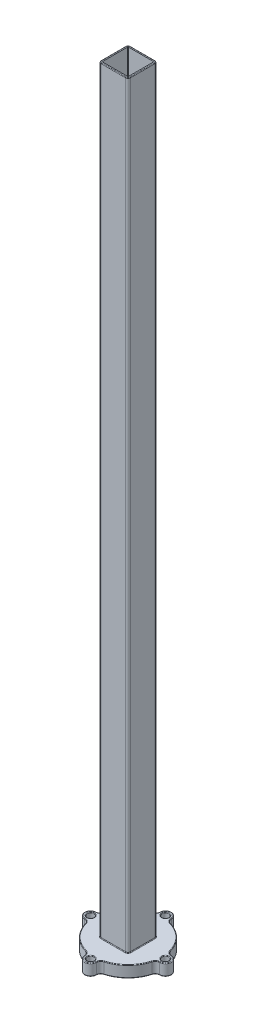
SolidWorks part; units mm, degrees
ref_plane "Front Plane" through (0, 0, 0) normal (0, 0, 1) x (1, 0, 0)
ref_plane "Top Plane" through (0, 0, 0) normal (0, 1, 0) x (1, 0, 0)
ref_plane "Right Plane" through (0, 0, 0) normal (1, 0, 0) x (0, 0, -1)
sketch "Sketch1" plane through (0, 0, 0) normal (0, 1, 0) x (1, 0, 0)
  line L0 (0, 0) -> (0, 32.3) construction
  line L1 (0, 0) -> (0, -32.3) construction
  line L2 (0, 0) -> (32.3, 0) construction
  line L3 (0, 0) -> (-32.3, 0) construction
  arc A0 (4.0756, 29.4036) -> (-4.0756, 29.4036) centre (0, 32.3) ccw
  arc A1 (-4.0756, -29.4036) -> (4.0756, -29.4036) centre (0, -32.3) ccw
  arc A2 (29.4036, -4.0756) -> (29.4036, 4.0756) centre (32.3, 0) ccw
  arc A3 (-29.4036, 4.0756) -> (-29.4036, -4.0756) centre (-32.3, 0) ccw
  arc A4 (-4.0756, 29.4036) -> (-29.4036, 4.0756) centre (0, 0) ccw
  arc A5 (29.4036, 4.0756) -> (4.0756, 29.4036) centre (0, 0) ccw
  arc A6 (4.0756, -29.4036) -> (29.4036, -4.0756) centre (0, 0) ccw
  arc A7 (-29.4036, -4.0756) -> (-4.0756, -29.4036) centre (0, 0) ccw
  dimension "D3" = 32.3
  dimension "D4" = 32.3
  dimension "D5" = 5
  dimension "D6" = 5
  dimension "D7" = 5
  dimension "D8" = 5
  dimension "D1" = 32.3
  dimension "D2" = 32.3
extrude "Boss-Extrude1" add sketch "Sketch1" along normal blind 10
sketch "Sketch2" plane through (0, 0, 0) normal (0, -1, 0) x (1, 0, 0)
  circle A0 centre (0, 0) radius 27.55
sketch "Sketch5" plane through (0, 0, 0) normal (0, -1, 0) x (-1, 0, 0)
  circle A0 centre (32.3, 0) radius 3
  circle A1 centre (0, 32.3) radius 3
  circle A2 centre (-32.3, 0) radius 3
  circle A3 centre (0, -32.3) radius 3
extrude "Cut-Extrude2" cut sketch "Sketch5" against normal through all contours A3 | A0 | A1 | A2
extrude "Cut-Extrude3" cut sketch "Sketch2" against normal blind 6.3 contours A0
sketch "Sketch8" plane through (0, 6.3, 0) normal (0, -1, 0) x (1, 0, 0)
  line L1 (12.6, -12.6) -> (-12.6, -12.6)
  line L2 (12.6, -12.6) -> (12.6, 12.6)
  line L3 (12.6, 12.6) -> (-12.6, 12.6)
  line L4 (-12.6, -12.6) -> (-12.6, 12.6)
  line L5 (12.6, -12.6) -> (-12.6, 12.6) construction
  line L6 (12.6, 12.6) -> (-12.6, -12.6) construction
  point P1 (0, 0)
  dimension "D1" = 25.2
  dimension "D2" = 25.2
extrude "Boss-Extrude2" add sketch "Sketch8" against normal blind 658
sketch "Sketch9" plane through (0, 664.3, 0) normal (0, 1, 0) x (1, 0, 0)
  line L1 (11.175, 11.175) -> (-11.175, 11.175)
  line L2 (11.175, 11.175) -> (11.175, -11.175)
  line L3 (11.175, -11.175) -> (-11.175, -11.175)
  line L4 (-11.175, 11.175) -> (-11.175, -11.175)
  line L5 (11.175, 11.175) -> (-11.175, -11.175) construction
  line L6 (11.175, -11.175) -> (-11.175, 11.175) construction
  point P0 (0, 0)
  dimension "D1" = 22.35
  dimension "D2" = 22.35
extrude "Cut-Extrude4" cut sketch "Sketch9" against normal through all
fillet "Fillet1" radius 2 4 edges at (12.6, 337.15, 12.6) (-12.6, 337.15, 12.6) (12.6, 337.15, -12.6) (-12.6, 337.15, -12.6)
fillet "Fillet2" radius 4 8 edges at (29.4036, 5, -4.0756) (29.4036, 5, 4.0756) (4.0756, 5, 29.4036) (-29.4036, 5, 4.0756) (-4.0756, 5, 29.4036) (-29.4036, 5, -4.0756) (-4.0756, 5, -29.4036) (4.0756, 5, -29.4036)
fillet "Fillet3" radius 0.5 49 edges at (30.0109, 10, 5.8364) (20.9902, 10, 20.9902) (5.8364, 10, 30.0109) (0, 10, 37.3) (-5.8364, 10, 30.0109) (-20.9902, 10, 20.9902) (-30.0109, 10, 5.8364) (-37.3, 10, 0) (-30.0109, 10, -5.8364) (-20.9902, 10, -20.9902) (-5.8364, 10, -30.0109) (0, 10, -37.3) (5.8364, 10, -30.0109) (20.9902, 10, -20.9902) (30.0109, 10, -5.8364) (37.3, 10, 0) (32.3, 10, -3) (0, 10, -35.3) (-32.3, 10, -3) (0, 10, 29.3) (-12.0142, 10, 12.0142) (0, 10, 12.6) (12.0142, 10, 12.0142) (12.6, 10, 0) (12.0142, 10, -12.0142) (0, 10, -12.6) (-12.0142, 10, -12.0142) (-12.6, 10, 0) (5.8364, 0, -30.0109) (0, 0, -37.3) (-5.8364, 0, -30.0109) (-20.9902, 0, -20.9902) (-30.0109, 0, -5.8364) (-37.3, 0, 0) (-30.0109, 0, 5.8364) (-20.9902, 0, 20.9902) (-5.8364, 0, 30.0109) (0, 0, 37.3) (5.8364, 0, 30.0109) (20.9902, 0, 20.9902) (30.0109, 0, 5.8364) (37.3, 0, 0) (30.0109, 0, -5.8364) (20.9902, 0, -20.9902) (32.3, 0, -3) (0, 0, -35.3) (-32.3, 0, -3) (0, 0, 29.3) (0, 0, -27.55)
fillet "Fillet4" radius 0.5 12 edges at (12.0142, 664.3, 12.0142) (12.6, 664.3, 0) (12.0142, 664.3, -12.0142) (0, 664.3, -12.6) (-12.0142, 664.3, -12.0142) (-12.6, 664.3, 0) (-12.0142, 664.3, 12.0142) (0, 664.3, 12.6) (-11.175, 335.3, -11.175) (11.175, 335.3, -11.175) (11.175, 335.3, 11.175) (-11.175, 335.3, 11.175)
